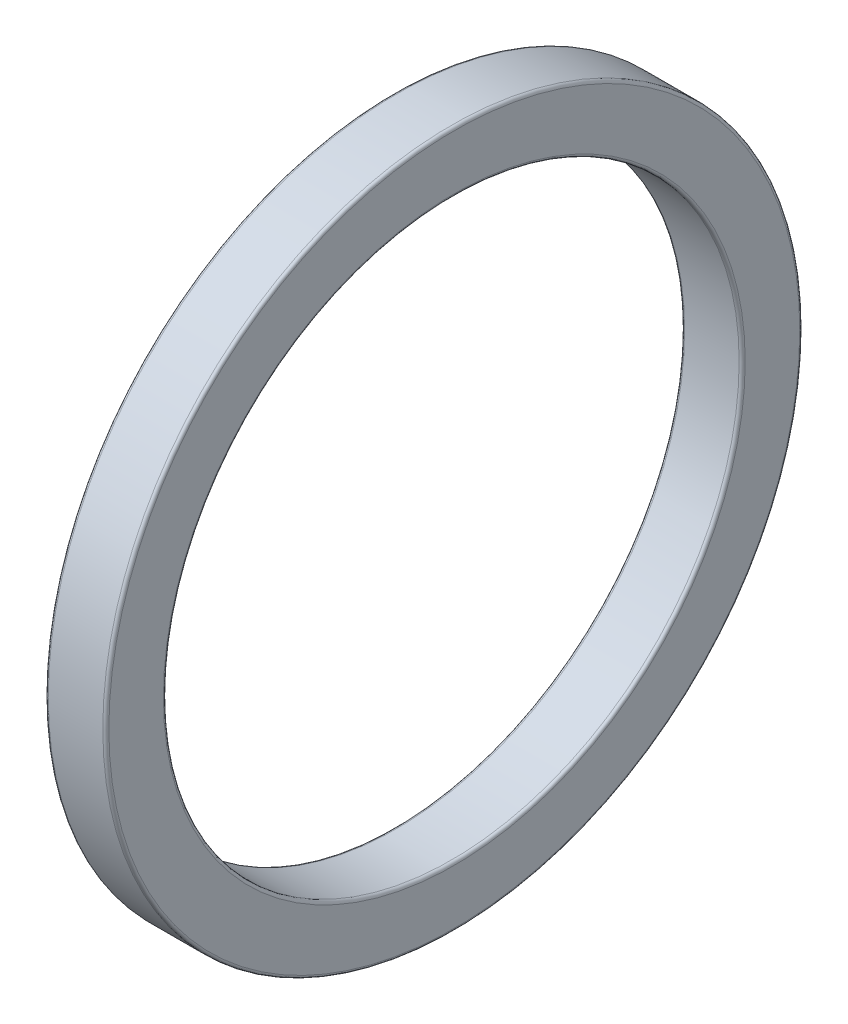
SolidWorks part; units mm, degrees
ref_plane "前视基准面" through (0, 0, 0) normal (0, 0, 1) x (1, 0, 0)
ref_plane "上视基准面" through (0, 0, 0) normal (0, 1, 0) x (1, 0, 0)
ref_plane "右视基准面" through (0, 0, 0) normal (1, 0, 0) x (0, 0, -1)
sketch "草图1" plane through (0, 0, 0) normal (0, 0, 1) x (1, 0, 0)
  line L0 (-16.5758, 0) -> (15, 0) construction
  line L1 (0, 19.1818) -> (0, -21.5455) construction
  line L2 (0, 9.5) -> (-2, 9.5)
  line L3 (-2, 9.5) -> (-2, 11.5)
  line L4 (-2, 11.5) -> (0, 11.5)
  line L5 (0, 11.5) -> (0, 9.5)
  dimension "D1" = 2
  dimension "D2" = 19
  dimension "D3" = 23
revolve "旋转1" add sketch "草图1" angle 360 about L0
fillet "圆角1" radius 0.1 4 edges at (-2, 0, 11.5) (-2, 0, 9.5) (0, 0, 9.5) (0, 0, 11.5)
